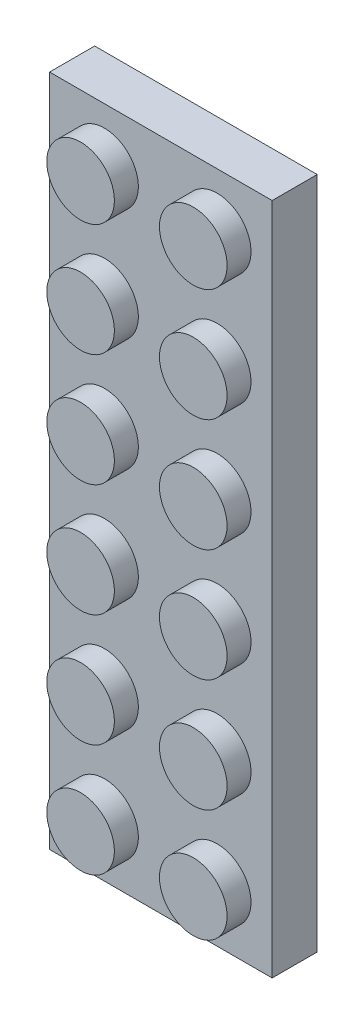
SolidWorks part; units mm, degrees
ref_plane "Спереди" through (0, 0, 0) normal (0, 0, 1) x (1, 0, 0)
ref_plane "Сверху" through (0, 0, 0) normal (0, 1, 0) x (1, 0, 0)
ref_plane "Справа" through (0, 0, 0) normal (1, 0, 0) x (0, 0, -1)
sketch "Эскиз1" plane through (0, 0, 0) normal (0, 0, 1) x (1, 0, 0)
  line L1 (-7.9, -23.9) -> (7.9, -23.9)
  line L2 (-7.9, -23.9) -> (-7.9, 23.9)
  line L3 (-7.9, 23.9) -> (7.9, 23.9)
  line L4 (7.9, -23.9) -> (7.9, 23.9)
  line L5 (-7.9, -23.9) -> (7.9, 23.9) construction
  line L6 (-7.9, 23.9) -> (7.9, -23.9) construction
  point P0 (0, 0)
  dimension "D1" = 15.8
  dimension "D2" = 47.8
extrude "Бобышка-Вытянуть1" add sketch "Эскиз1" along normal blind 3.2
sketch "Эскиз2" plane through (0, 0, 3.2) normal (0, 0, 1) x (1, 0, 0)
  line L0 (7.9, 23.9) -> (-7.9, 23.9) construction
  line L1 (-7.9, 23.9) -> (-7.9, -23.9) construction
  circle A0 centre (-4, 20) radius 2.4
  circle A1 centre (4, 20) radius 2.4
  circle A2 centre (4, 12) radius 2.4
  circle A3 centre (4, 4) radius 2.4
  circle A4 centre (4, -4) radius 2.4
  circle A5 centre (4, -12) radius 2.4
  circle A6 centre (4, -20) radius 2.4
  circle A7 centre (-4, 12) radius 2.4
  circle A8 centre (-4, 4) radius 2.4
  circle A9 centre (-4, -4) radius 2.4
  circle A10 centre (-4, -12) radius 2.4
  circle A11 centre (-4, -20) radius 2.4
  dimension "D1" = 3.9
  dimension "D2" = 3.9
  dimension "D3" = 2
  dimension "D4" = 6
extrude "Бобышка-Вытянуть2" add sketch "Эскиз2" along normal blind 1.7
sketch "Эскиз3" plane through (0, 0, 0) normal (0, 0, -1) x (-1, 0, 0)
  line L0 (-7.9, -23.9) -> (-7.9, 23.9) construction
  line L1 (-7.9, 23.9) -> (7.9, 23.9) construction
  circle A0 centre (-4, 20) radius 2.5
  circle A1 centre (4, 20) radius 2.5
  circle A2 centre (4, 12) radius 2.5
  circle A3 centre (4, 4) radius 2.5
  circle A4 centre (4, -4) radius 2.5
  circle A5 centre (4, -12) radius 2.5
  circle A6 centre (4, -20) radius 2.5
  circle A7 centre (-4, 12) radius 2.5
  circle A8 centre (-4, 4) radius 2.5
  circle A9 centre (-4, -4) radius 2.5
  circle A10 centre (-4, -12) radius 2.5
  circle A11 centre (-4, -20) radius 2.5
  dimension "D1" = 3.9
  dimension "D3" = 2
  dimension "D2" = 3.9
  dimension "D4" = 6
extrude "Вырез-Вытянуть2" cut sketch "Эскиз3" against normal blind 1.8
